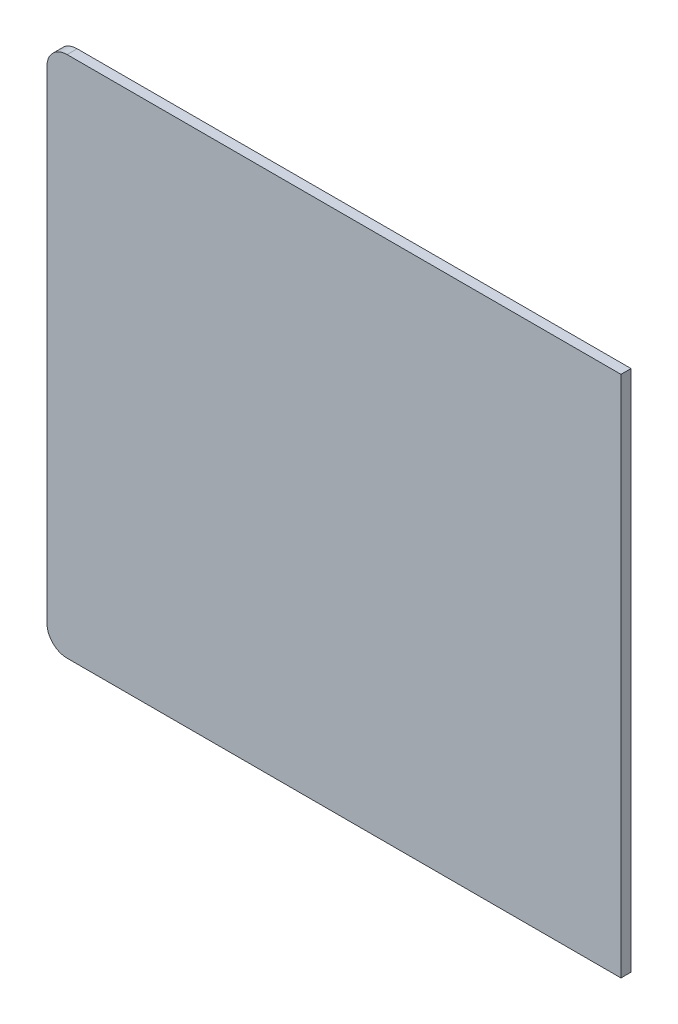
SolidWorks part; units mm, degrees
material "Thornel Mat VMA"
ref_plane "Front Plane" through (0, 0, 0) normal (0, 0, 1) x (1, 0, 0)
ref_plane "Top Plane" through (0, 0, 0) normal (0, 1, 0) x (1, 0, 0)
ref_plane "Right Plane" through (0, 0, 0) normal (1, 0, 0) x (0, 0, -1)
sketch "Sketch1" plane through (0, 0, 0) normal (0, 0, 1) x (1, 0, 0)
  line L1 (-125, -130) -> (125, -130)
  line L2 (-125, -130) -> (-125, 130)
  line L3 (-125, 130) -> (125, 130)
  line L4 (125, -130) -> (125, 130)
  line L5 (-125, -130) -> (125, 130) construction
  line L6 (-125, 130) -> (125, -130) construction
  point P0 (0, 0)
  dimension "D1" = 260
  dimension "D2" = 250
extrude "Boss-Extrude1" add sketch "Sketch1" along normal blind 5
fillet "Fillet1" radius 10 2 edges at (-125, -130, 2.5) (-125, 130, 2.5)
sketch "Sketch2" plane through (0, 0, 0) normal (0, 0, -1) x (-1, 0, 0)
  line L0 (-125, 130) -> (115, 130) construction
  line L1 (-125, -130) -> (-160.4742, -130)
  line L2 (-125, -130) -> (-125, 130)
  line L3 (-125, 130) -> (-160.4742, 130)
  line L4 (-160.4742, -130) -> (-160.4742, 130)
  line L5 (-160.4742, -130) -> (-160.4742, -110) construction
extrude "Boss-Extrude2" add sketch "Sketch2" against normal up to surface (5 mm away) up to face at (-39.0237, 0, 5)
